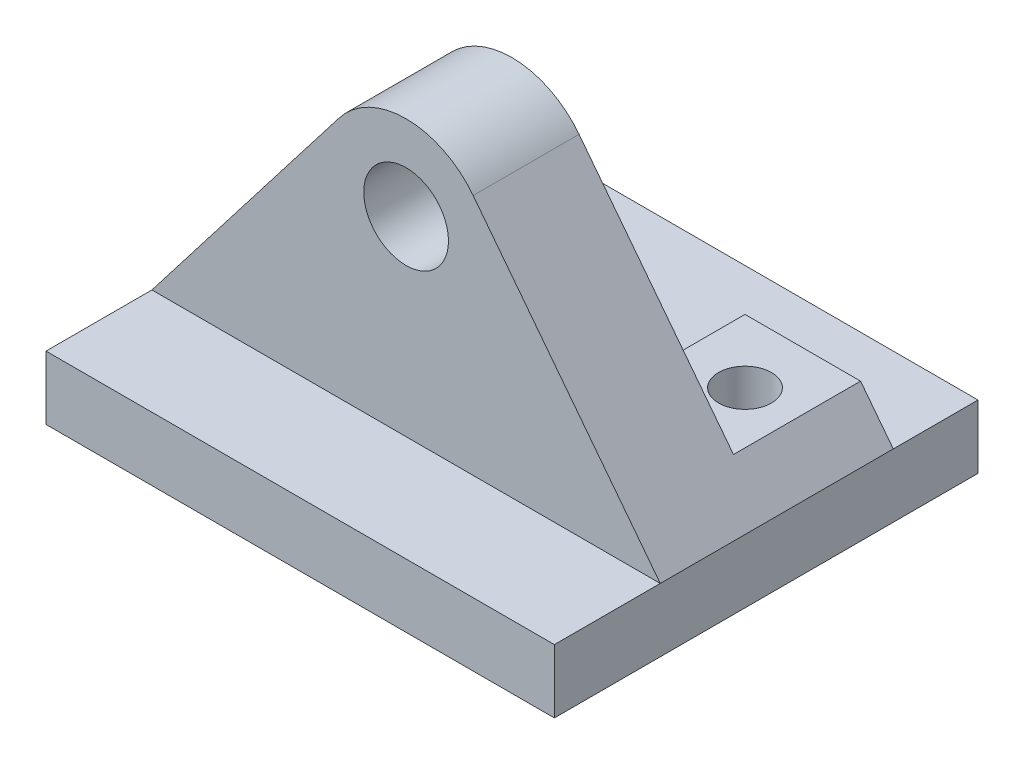
SolidWorks part; units mm, degrees
ref_plane "Front" through (0, 0, 0) normal (0, 0, 1) x (1, 0, 0)
ref_plane "Top" through (0, 0, 0) normal (0, 1, 0) x (1, 0, 0)
ref_plane "Right" through (0, 0, 0) normal (1, 0, 0) x (0, 0, -1)
sketch "Sketch1" plane through (0, 0, 0) normal (0, 0, 1) x (1, 0, 0)
  line L0 (0, 0) -> (24, 0)
  line L1 (12, 12) -> (12, 0) construction
  line L2 (0, 0) -> (0, 3)
  line L3 (0, 3) -> (8.8336, 14.4441)
  line L4 (24, 3) -> (15.1664, 14.4441)
  line L5 (24, 0) -> (24, 3)
  circle A0 centre (12, 12) radius 6 construction
  circle A1 centre (12, 12) radius 2
  arc A2 (15.1664, 14.4441) -> (8.8336, 14.4441) centre (12, 12) ccw
  dimension "D1" = 12
  dimension "D2" = 4
  dimension "D3" = 8
  dimension "D4" = 12
  dimension "D5" = 12
  dimension "D6" = 3
extrude "Boss-Extrude1" add sketch "Sketch1" along normal blind 15
sketch "Sketch2" plane through (24, 0, 0) normal (1, 0, 0) x (0, 0, -1)
  line L0 (-15, 3) -> (-15, 14.4441) construction
  line L1 (-10, 26.7878) -> (0, 26.7878)
  line L2 (-10, 26.7878) -> (-10, 3)
  line L3 (-10, 3) -> (0, 3)
  line L4 (0, 26.7878) -> (0, 3)
  line L5 (-15, 3) -> (0, 3) construction
  line L6 (0, 0) -> (0, 3) construction
  dimension "D1" = 5
extrude "Cut-Extrude1" cut sketch "Sketch2" against normal through all
sketch "Sketch5" plane through (0, 3, 0) normal (0, 1, 0) x (-1, 0, 0)
  line L0 (0, 10) -> (0, 0) construction
  line L1 (-24, 10) -> (-17, 10)
  line L2 (-24, 10) -> (-24, 4)
  line L3 (-24, 4) -> (-17, 4)
  line L4 (-17, 10) -> (-17, 4)
  line L5 (0, 10) -> (-7, 10)
  line L6 (0, 10) -> (0, 4)
  line L7 (0, 4) -> (-7, 4)
  line L8 (-7, 10) -> (-7, 4)
  line L9 (0, 10) -> (-24, 10) construction
  dimension "D1" = 6
  dimension "D2" = 10
extrude "Boss-Extrude3" add sketch "Sketch5" along normal blind 2
sketch "Sketch3" plane through (0, 0, 0) normal (0, -1, 0) x (1, 0, 0)
  line L0 (20, 7) -> (4, 7) construction
  line L3 (12, 7) -> (12, 0) construction
  line L4 (0, 0) -> (24, 0) construction
  circle A0 centre (4, 7) radius 1.25
  circle A1 centre (20, 7) radius 1.25
  dimension "D1" = 2.5
  dimension "D2" = 7
  dimension "D4" = 16
extrude "Cut-Extrude2" cut sketch "Sketch3" against normal through all
cosmetic thread "Cosmetic Thread1" parameters "D2"=3
cosmetic thread "Cosmetic Thread2" parameters "D2"=3
sketch "Sketch4" plane through (0, 14, 15) normal (0, 0, -1) x (1, 0, 0)
  line L1 (0, 14) -> (24, 14)
  line L2 (0, 14) -> (0, 11)
  line L3 (0, 11) -> (24, 11)
  line L4 (24, 14) -> (24, 11)
  line L5 (24, 14) -> (24, 11) construction
  dimension "D1" = 3
extrude "Boss-Extrude2" add sketch "Sketch4" against normal blind 5
sketch "Sketch6" plane through (0, 0, 10) normal (0, 0, 1) x (1, 0, 0)
  line L3 (0, 5) -> (0, 3)
  line L4 (0, 3) -> (1.5438, 5)
  line L5 (1.5438, 5) -> (0, 5)
  line L6 (0, 5) -> (0, 3)
  line L7 (0, 3) -> (1.5438, 5)
  line L8 (1.5438, 5) -> (0, 5)
  line L9 (24, 5) -> (22.4562, 5)
  line L10 (22.4562, 5) -> (24, 3)
  line L11 (24, 3) -> (24, 5)
  line L12 (24, 5) -> (22.4562, 5)
  line L13 (22.4562, 5) -> (24, 3)
  line L14 (24, 3) -> (24, 5)
  dimension "D1" = 0
  dimension "D2" = 0
extrude "Cut-Extrude3" cut sketch "Sketch6" against normal through all
